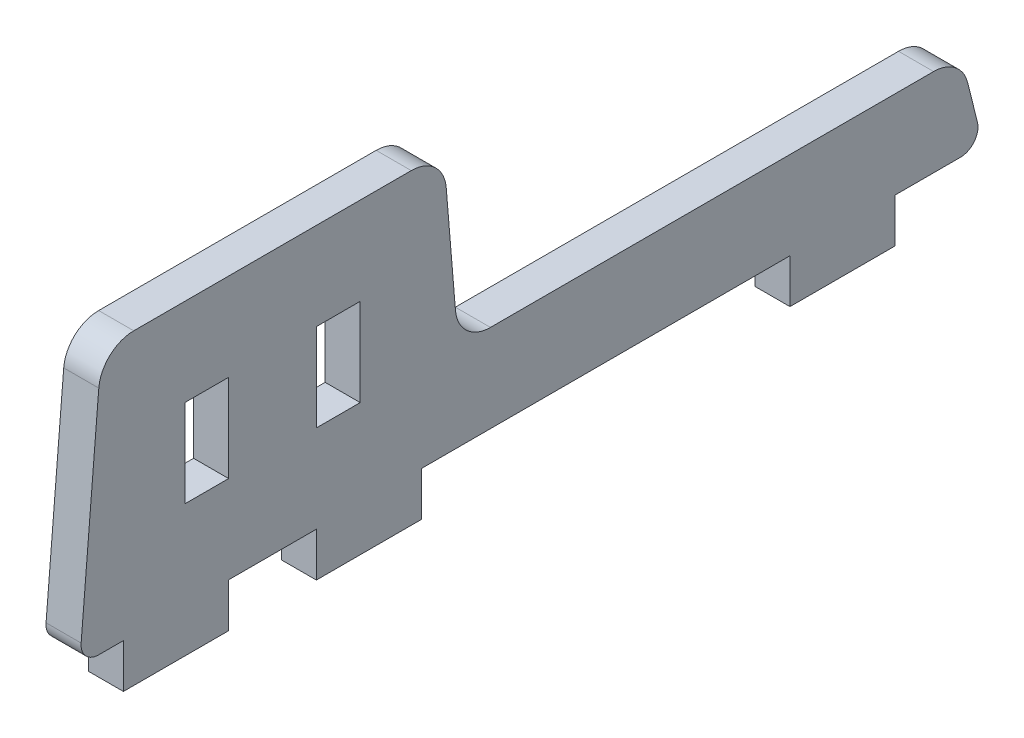
SolidWorks part; units mm, degrees
ref_plane "Front Plane" through (0, 0, 0) normal (0, 0, 1) x (1, 0, 0)
ref_plane "Top Plane" through (0, 0, 0) normal (0, 1, 0) x (1, 0, 0)
ref_plane "Right Plane" through (0, 0, 0) normal (1, 0, 0) x (0, 0, -1)
sketch "Sketch1" plane through (0, 0, 0) normal (1, 0, 0) x (0, 0, -1)
  line L0 (-46.5, -15) -> (-46.5, -20.0256)
  line L1 (-49, 15) -> (-10, 15)
  line L3 (-51.5, -15) -> (-46.5, -15)
  line L5 (-34.5, -15) -> (-24.5, -15)
  line L6 (-12.5, -15) -> (29.5, -15)
  line L7 (-46.5, -20.0256) -> (-34.5, -20.0256)
  line L8 (-34.5, -20.0256) -> (-34.5, -15)
  line L9 (-24.5, -15) -> (-24.5, -20.0256)
  line L10 (-12.5, -20.0256) -> (-12.5, -15)
  line L11 (-24.5, -20.0256) -> (-12.5, -20.0256)
  line L12 (29.5, -20.0256) -> (41.5, -20.0256)
  line L13 (41.5, -20.0256) -> (41.5, -15)
  line L14 (29.5, -15) -> (29.5, -20.0256)
  line L15 (-8.3333, -5) -> (49, -5)
  line L16 (-51.5, -15) -> (-49, 15)
  line L17 (-8.3333, -5) -> (-10, 15)
  line L18 (51.5, -15) -> (49, -5)
  line L19 (41.5, -15) -> (51.5, -15)
  line L20 (55, 0) -> (-55, 0) construction
  line L21 (0, 55) -> (0, -55) construction
  line L22 (-24.5, 5) -> (-19.5, 5)
  line L23 (-24.5, 5) -> (-24.5, -5)
  line L24 (-39.5, 5) -> (-34.5, 5)
  line L25 (-39.5, 5) -> (-39.5, -5)
  line L26 (-39.5, -5) -> (-34.5, -5)
  line L27 (-34.5, 5) -> (-34.5, -5)
  line L28 (-39.5, 5) -> (-34.5, -5) construction
  line L29 (-39.5, -5) -> (-34.5, 5) construction
  line L30 (-24.5, -5) -> (-19.5, -5)
  line L31 (-19.5, 5) -> (-19.5, -5)
  point P0 (0, 0)
  point P25 (-37, 0)
  dimension "D1" = 103
  dimension "D2" = 57.3333
  dimension "D3" = 5.0256
  dimension "D4" = 12
  dimension "D5" = 5
  dimension "D7" = 10
  dimension "D9" = 10
  dimension "D10" = 10
  dimension "D11" = 20
  dimension "D12" = 20.0256
  dimension "D13" = 39
  dimension "D14" = 49
  dimension "D15" = 10
  dimension "D16" = 51.5
  dimension "D17" = 5
  dimension "D18" = 10
  dimension "D19" = 10
  dimension "D21" = 10
  dimension "D6" = 2
  dimension "D8" = 2
  dimension "D20" = 2
extrude "Boss-Extrude1" add sketch "Sketch1" along normal blind 4
fillet "Fillet2" radius 4 4 edges at (2, -5, 8.3333) (2, -5, -49) (2, 15, 10) (2, 15, 49)
fillet "Fillet4" radius 2 2 edges at (2, -15, -51.5) (2, -15, 51.5)
